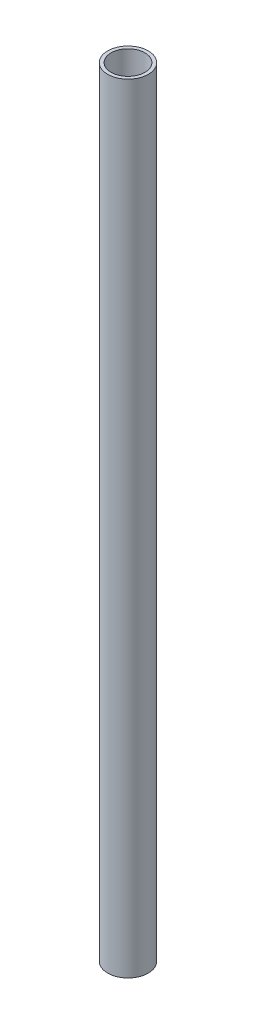
SolidWorks part; units mm, degrees
ref_plane "前视基准面" through (0, 0, 0) normal (0, 0, 1) x (1, 0, 0)
ref_plane "上视基准面" through (0, 0, 0) normal (0, 1, 0) x (1, 0, 0)
ref_plane "右视基准面" through (0, 0, 0) normal (1, 0, 0) x (0, 0, -1)
sketch "草图1" plane through (0, 0, 0) normal (0, 1, 0) x (1, 0, 0)
  circle A0 centre (0, 0) radius 5
  circle A1 centre (0, 0) radius 6
  dimension "D1" = 12
  dimension "D2" = 10
extrude "凸台-拉伸1" add sketch "草图1" along normal blind 230
